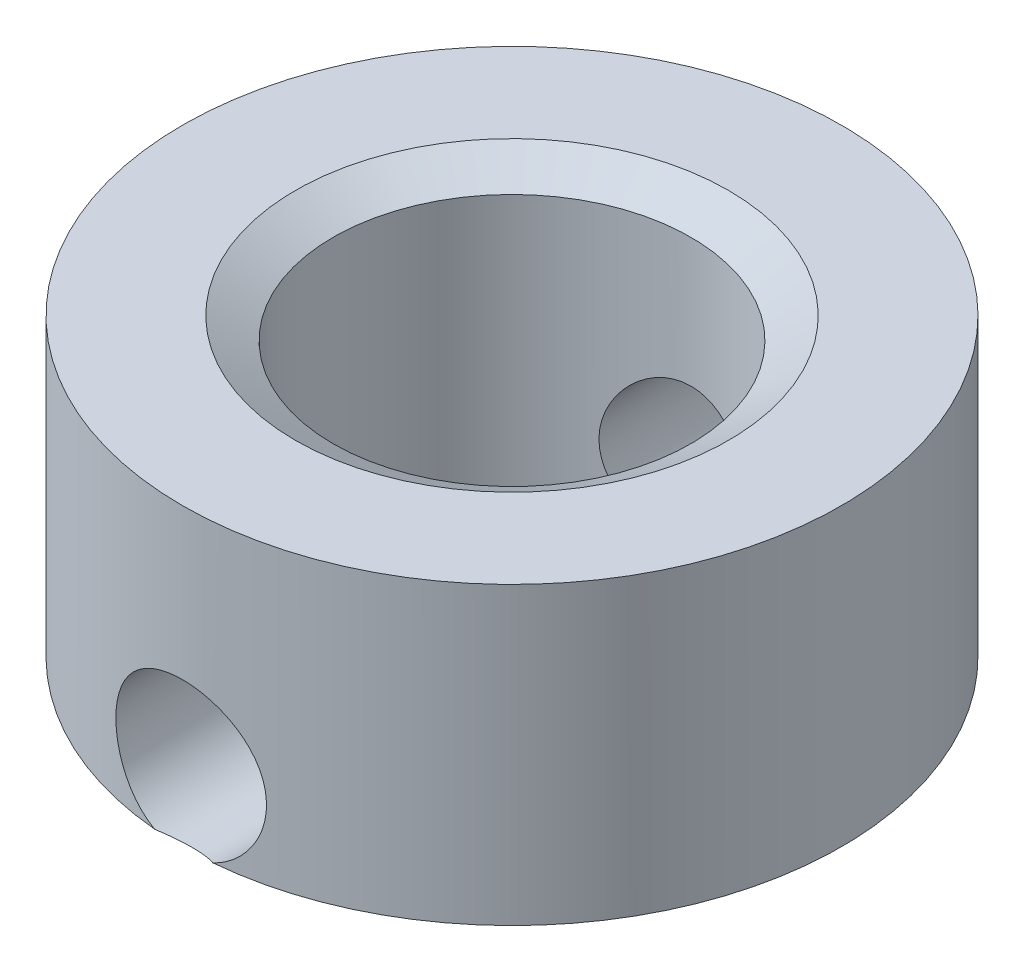
SolidWorks part; units mm, degrees
ref_plane "Front Plane" through (0, 0, 0) normal (0, 0, 1) x (1, 0, 0)
ref_plane "Top Plane" through (0, 0, 0) normal (0, 1, 0) x (1, 0, 0)
ref_plane "Right Plane" through (0, 0, 0) normal (1, 0, 0) x (0, 0, -1)
sketch "Sketch1" plane through (0, 0, 0) normal (0, 1, 0) x (1, 0, 0)
  circle A0 centre (0, 0) radius 2.375
  circle A1 centre (0, 0) radius 4.375
  dimension "D1" = 4.75
  dimension "D2" = 2
extrude "Boss-Extrude1" add sketch "Sketch1" along normal blind 4.5
chamfer "Chamfer1" distance 0.5 angle 30 1 edges at (0, 4.5, 2.375)
chamfer "Chamfer2" distance 1 angle 30 1 edges at (0, 0, 4.375)
sketch "Sketch2" plane through (0, 0, 0) normal (0, 0, 1) x (1, 0, 0)
  line L0 (-2.265, -4) -> (2.265, -4) construction
  circle A0 centre (0, 1.5) radius 1
  dimension "D1" = 2
  dimension "D2" = 5.5
extrude "Cut-Extrude1" cut sketch "Sketch2" against normal through all both and the other way through all
